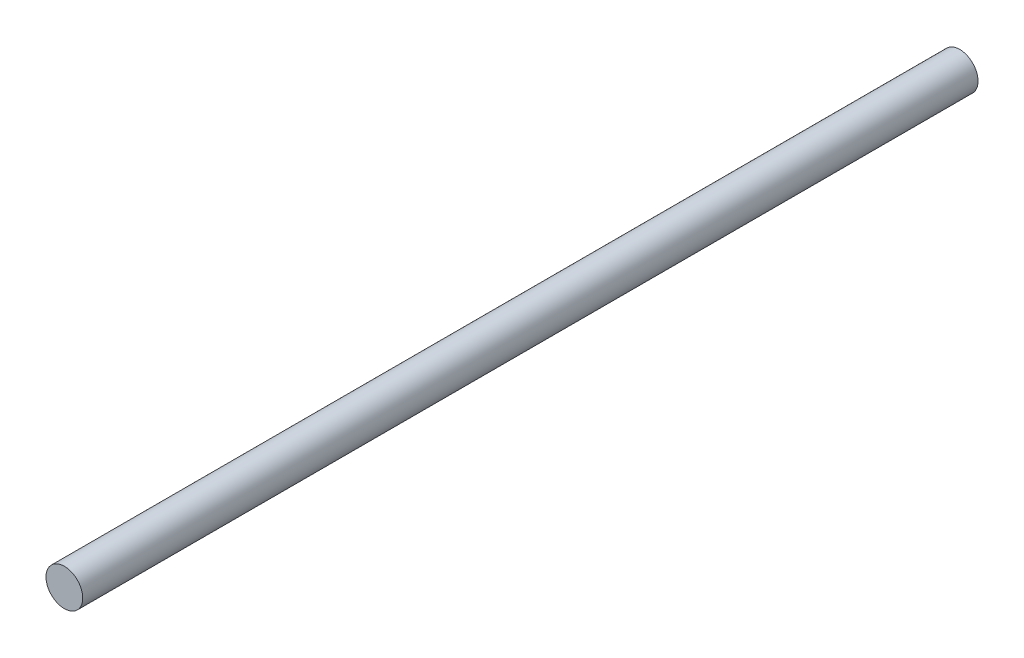
SolidWorks part; units mm, degrees
ref_plane "Front Plane" through (0, 0, 0) normal (0, 0, 1) x (1, 0, 0)
ref_plane "Top Plane" through (0, 0, 0) normal (0, 1, 0) x (1, 0, 0)
ref_plane "Right Plane" through (0, 0, 0) normal (1, 0, 0) x (0, 0, -1)
sketch "Sketch1" plane through (0, 0, 0) normal (0, 0, 1) x (1, 0, 0)
  circle A0 centre (0, 0) radius 25
  dimension "D1" = 50
extrude "Boss-Extrude1" add sketch "Sketch1" along normal blind 1219.2
